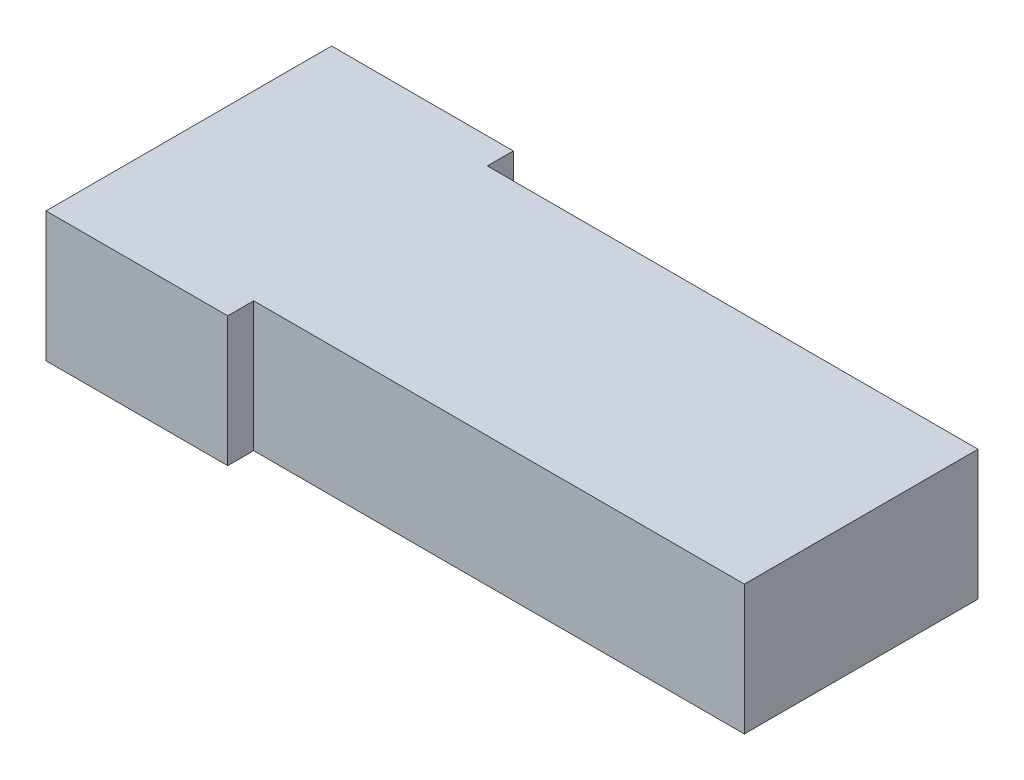
SolidWorks part; units mm, degrees
ref_plane "Front Plane" through (0, 0, 0) normal (0, 0, 1) x (1, 0, 0)
ref_plane "Top Plane" through (0, 0, 0) normal (0, 1, 0) x (1, 0, 0)
ref_plane "Right Plane" through (0, 0, 0) normal (1, 0, 0) x (0, 0, -1)
sketch "Sketch1" plane through (0, 0, 0) normal (0, 1, 0) x (1, 0, 0)
  line L1 (-7.5, -4.5) -> (7.5, -4.5)
  line L3 (-7.5, 4.5) -> (7.5, 4.5)
  line L5 (-7.5, -4.5) -> (7.5, 4.5) construction
  line L6 (-7.5, 4.5) -> (7.5, -4.5) construction
  line L10 (-7.5, 4.5) -> (-7.5, 5.5)
  line L11 (-7.5, 5.5) -> (-14.5, 5.5)
  line L12 (-14.5, 5.5) -> (-14.5, -5.5)
  line L13 (-14.5, -5.5) -> (-7.5, -5.5)
  line L14 (-7.5, -5.5) -> (-7.5, -4.5)
  line L16 (7.5, 4.5) -> (11.4, 4.5)
  line L17 (11.4, 4.5) -> (11.4, -4.5)
  line L18 (11.4, -4.5) -> (7.5, -4.5)
  point P0 (0, 0)
  dimension "D1" = 9
  dimension "D2" = 15
  dimension "D3" = 3.9
  dimension "D6" = 1
  dimension "D7" = 7
extrude "Boss-Extrude1" add sketch "Sketch1" along normal blind 2
sketch "Sketch2" plane through (0, 0, 0) normal (0, 1, 0) x (1, 0, 0)
  line L0 (6.1, 4.5) -> (-7.5, 4.5)
  line L1 (-7.5, 4.5) -> (-7.5, 5.5)
  line L2 (-7.5, 5.5) -> (-14.5, 5.5)
  line L3 (-14.5, 5.5) -> (-14.5, 3.5)
  line L4 (-14.5, 5.5) -> (-14.5, -5.5) construction
  line L5 (-14.5, 3.5) -> (0.5, 3.5)
  line L6 (0.5, 3.5) -> (0.5, 3)
  line L12 (-7.5, -4.5) -> (-7.5, -5.5)
  line L13 (-7.5, -5.5) -> (-14.5, -5.5)
  line L14 (-14.5, -5.5) -> (-14.5, -3.5)
  line L15 (-14.5, -3.5) -> (0.5, -3.5)
  line L16 (0.5, -3.5) -> (0.5, -3)
  line L23 (0.5, -1.6) -> (0.5, 1.6)
  line L24 (-7.5, -4.5) -> (7.5, -4.5)
  line L25 (-7.5, -4.5) -> (11.4, -4.5) construction
  line L27 (7.5, -3) -> (0.5, -3)
  line L37 (7.5, -4.5) -> (11.4, -4.5)
  line L38 (11.4, -4.5) -> (11.4, 4.5)
  line L39 (11.4, 4.5) -> (9.9, 4.5)
  line L40 (11.4, 4.5) -> (-7.5, 4.5) construction
  line L41 (9.9, 4.5) -> (9.9, -3)
  line L42 (9.9, -3) -> (7.5, -3)
  line L43 (0.5, -1.6) -> (7.5, -1.6)
  line L44 (7.5, -1.6) -> (8.5, -1.6)
  line L45 (8.5, -1.6) -> (8.5, 4.5)
  line L46 (8.5, 4.5) -> (7.5, 4.5)
  line L47 (7.5, 4.5) -> (7.5, 1.6)
  line L51 (6.1, 4.5) -> (6.1, 3)
  line L52 (6.1, 3) -> (0.5, 3)
  line L53 (0.5, 1.6) -> (7.5, 1.6)
  dimension "D1" = 1.4
  dimension "D2" = 7
  dimension "D3" = 1.5
  dimension "D4" = 1.4
  dimension "D5" = 2
  dimension "D6" = 1.5
  dimension "D7" = 1.4
  dimension "D8" = 1
extrude "Boss-Extrude2" add sketch "Sketch2" against normal blind 3
sketch "Sketch3" plane through (0, -3, 0) normal (0, -1, 0) x (1, 0, 0)
  line L0 (-14.5, 5.5) -> (-14.5, 2.3911)
  line L1 (-14.5, -3.5) -> (-14.5, 3.5) construction
  line L2 (-7.5, 5.5) -> (-14.5, 5.5)
  line L3 (-7.5, 5.5) -> (-7.5, 2.3911)
  line L4 (-7.5, 2.3911) -> (-14.5, 2.3911)
  line L5 (-7.5, -5.5) -> (-14.5, -5.5)
  line L6 (-14.5, -5.5) -> (-14.5, -2.3911)
  line L7 (-7.5, -5.5) -> (-7.5, -2.3911)
  line L8 (-7.5, -2.3911) -> (-14.5, -2.3911)
  dimension "D1" = 3.1089
extrude "Boss-Extrude3" add sketch "Sketch3" against normal blind 2
